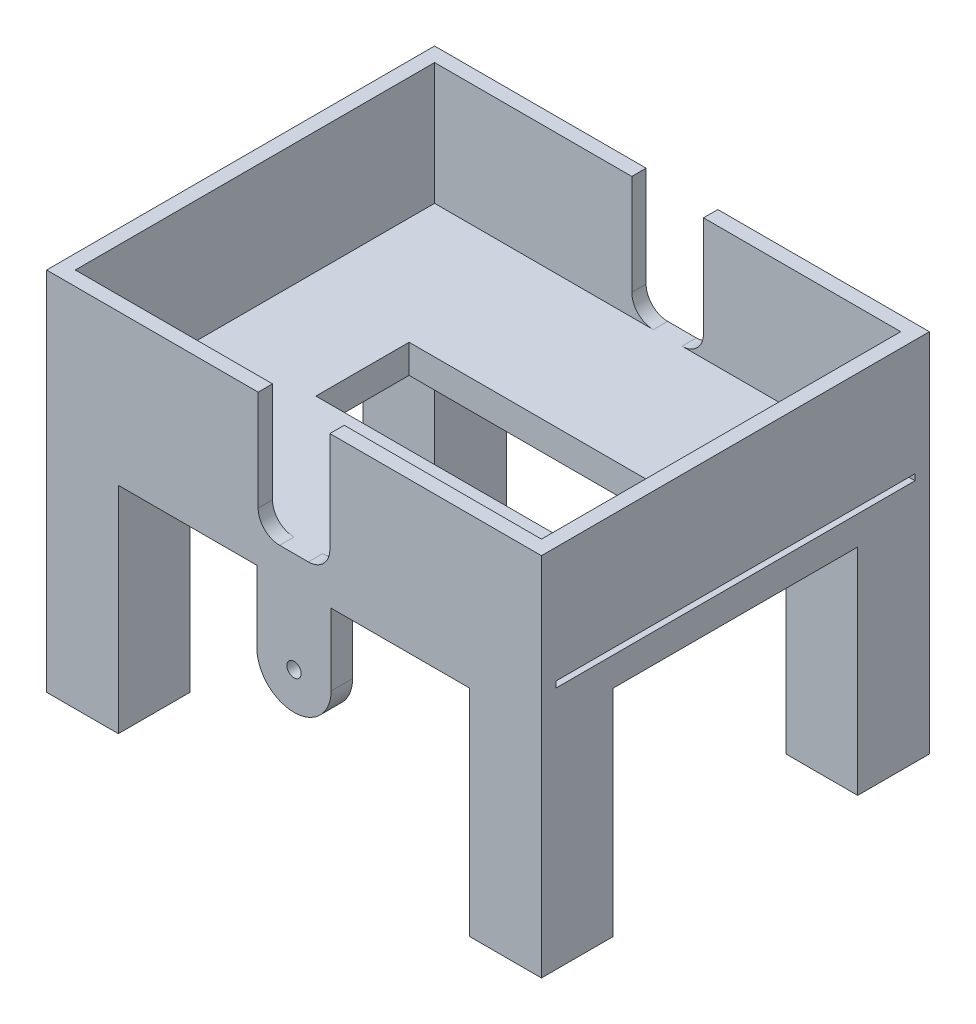
SolidWorks part; units mm, degrees
ref_plane "Front Plane" through (0, 0, 0) normal (0, 0, 1) x (1, 0, 0)
ref_plane "Top Plane" through (0, 0, 0) normal (0, 1, 0) x (1, 0, 0)
ref_plane "Right Plane" through (0, 0, 0) normal (1, 0, 0) x (0, 0, -1)
sketch "Sketch5" plane through (0, 0, 0) normal (0, 1, 0) x (1, 0, 0)
  line L1 (0, 127.254) -> (165.1, 127.254)
  line L2 (0, 127.254) -> (0, 0)
  line L3 (0, 0) -> (165.1, 0)
  line L4 (165.1, 127.254) -> (165.1, 0)
  line L5 (-5.08, 132.334) -> (170.18, 132.334)
  line L6 (-5.08, 132.334) -> (-5.08, -5.08)
  line L7 (-5.08, -5.08) -> (170.18, -5.08)
  line L8 (170.18, 132.334) -> (170.18, -5.08)
  dimension "D1" = 165.1
  dimension "D2" = 127.254
  dimension "D3" = 5.08
  dimension "D4" = 5.08
  dimension "D5" = 5.08
  dimension "D6" = 5.08
extrude "Boss-Extrude2" add sketch "Sketch5" along normal blind 43.18
sketch "Sketch7" plane through (0, 0, 0) normal (0, 1, 0) x (1, 0, 0)
  line L0 (-5.08, -5.08) -> (170.18, -5.08) construction
  line L1 (-5.08, -5.08) -> (170.18, -5.08)
  line L2 (-5.08, -5.08) -> (-5.08, 132.334)
  line L3 (-5.08, 132.334) -> (170.18, 132.334)
  line L4 (170.18, -5.08) -> (170.18, 132.334)
extrude "Boss-Extrude4" add sketch "Sketch7" against normal blind 10.16
sketch "Sketch9" plane through (170.18, 0, 0) normal (1, 0, 0) x (0, 0, -1)
  line L0 (127.254, 0) -> (0, 0) construction
  line L1 (0, 0) -> (127.254, 0)
  line L2 (0, 0) -> (0, 2.159)
  line L3 (0, 2.159) -> (127.254, 2.159)
  line L4 (127.254, 0) -> (127.254, 2.159)
  dimension "D1" = 127.254
  dimension "D2" = 2.159
extrude "Cut-Extrude1" cut sketch "Sketch9" against normal blind 8.128
sketch "Sketch10" plane through (0, 0, 5.08) normal (0, 0, 1) x (1, 0, 0)
  line L0 (170.18, 43.18) -> (170.18, -10.16) construction
  line L1 (69.85, 43.18) -> (95.25, 43.18)
  line L2 (69.85, 43.18) -> (69.85, 7.62)
  line L3 (77.47, 0) -> (87.63, 0)
  line L4 (95.25, 43.18) -> (95.25, 7.62)
  line L5 (82.55, 0) -> (82.55, 43.18) construction
  line L6 (-5.08, 43.18) -> (170.18, 43.18) construction
  arc A0 (87.63, 0) -> (95.25, 7.62) centre (87.63, 7.62) ccw
  arc A1 (69.85, 7.62) -> (77.47, 0) centre (77.47, 7.62) ccw
  point P16 (95.25, 0)
  point P20 (82.55, 0)
  dimension "D5" = 7.62
  dimension "D6" = 7.62
  dimension "D1" = 25.4
  dimension "D2" = 12.7
  dimension "D3" = 87.63
  dimension "D4" = 43.18
extrude "Cut-Extrude2" cut sketch "Sketch10" against normal blind 147.066 and the other way blind 13.208
sketch "Sketch11" plane through (0, -10.16, 0) normal (0, -1, 0) x (1, 0, 0)
  line L1 (38.1, -80.137) -> (127, -80.137)
  line L2 (38.1, -80.137) -> (38.1, -47.117)
  line L3 (38.1, -47.117) -> (127, -47.117)
  line L4 (127, -80.137) -> (127, -47.117)
  line L6 (38.1, -63.627) -> (126.7086, -63.627) construction
  line L8 (87.63, -132.334) -> (77.47, -132.334) construction
  line L9 (82.55, -80.137) -> (82.55, -48.1628) construction
  line L12 (170.18, 5.08) -> (170.18, -132.334) construction
  dimension "D1" = 33.02
  dimension "D2" = 88.9
  dimension "D3" = 68.707
  dimension "D4" = 87.63
extrude "Cut-Extrude3" cut sketch "Sketch11" against normal blind 10.16
sketch "Sketch12" plane through (0, -10.16, 0) normal (0, -1, 0) x (1, 0, 0)
  line L0 (-5.08, 5.08) -> (170.18, 5.08) construction
  line L1 (-5.08, 5.08) -> (20.32, 5.08)
  line L2 (-5.08, 5.08) -> (-5.08, -20.32)
  line L3 (-5.08, -20.32) -> (20.32, -20.32)
  line L4 (20.32, 5.08) -> (20.32, -20.32)
  line L5 (-5.08, -132.334) -> (-5.08, 5.08) construction
  line L6 (170.18, -63.627) -> (-5.08, -63.627) construction
  line L7 (144.78, 5.08) -> (144.78, -20.32)
  line L8 (144.78, 5.08) -> (170.18, 5.08)
  line L9 (170.18, 5.08) -> (170.18, -20.32)
  line L10 (144.78, -20.32) -> (170.18, -20.32)
  line L11 (170.18, 5.08) -> (170.18, -132.334) construction
  line L12 (144.78, -132.334) -> (170.18, -132.334)
  line L13 (170.18, -132.334) -> (170.18, -106.934)
  line L14 (144.78, -106.934) -> (170.18, -106.934)
  line L15 (144.78, -132.334) -> (144.78, -106.934)
  line L16 (-5.08, -106.934) -> (20.32, -106.934)
  line L17 (20.32, -132.334) -> (20.32, -106.934)
  line L18 (-5.08, -132.334) -> (20.32, -132.334)
  line L19 (-5.08, -132.334) -> (-5.08, -106.934)
  dimension "D1" = 25.4
  dimension "D2" = 25.4
  dimension "D3" = 2
extrude "Boss-Extrude5" add sketch "Sketch12" along normal blind 76.2
sketch "Sketch13" plane through (0, -86.36, 0) normal (0, -1, 0) x (1, 0, 0)
  line L0 (20.32, -20.32) -> (20.32, 5.08) construction
  line L1 (-2.54, 2.54) -> (17.78, 2.54)
  line L2 (-2.54, 2.54) -> (-2.54, -17.78)
  line L3 (-2.54, -17.78) -> (17.78, -17.78)
  line L4 (17.78, 2.54) -> (17.78, -17.78)
  line L5 (-5.08, -20.32) -> (20.32, -20.32) construction
  line L6 (-5.08, -7.62) -> (20.32, -7.62) construction
  line L7 (7.62, -20.32) -> (7.62, 5.08) construction
  line L8 (-5.08, 5.08) -> (-5.08, -20.32) construction
  line L9 (20.32, -20.32) -> (20.32, 5.08) construction
  line L10 (20.32, 5.08) -> (-5.08, 5.08) construction
  line L11 (-5.08, -20.32) -> (20.32, -20.32) construction
  line L12 (147.32, 2.54) -> (147.32, -17.78)
  line L13 (147.32, 2.54) -> (167.64, 2.54)
  line L14 (167.64, 2.54) -> (167.64, -17.78)
  line L15 (147.32, -17.78) -> (167.64, -17.78)
  line L16 (157.48, -20.32) -> (157.48, 5.08) construction
  line L17 (144.78, -7.62) -> (170.18, -7.62) construction
  line L18 (-5.08, -63.627) -> (170.18, -63.627) construction
  line L19 (-5.08, -106.934) -> (-5.08, -20.32) construction
  line L20 (170.18, -20.32) -> (170.18, -106.934) construction
  line L21 (147.32, -109.474) -> (167.64, -109.474)
  line L22 (147.32, -129.794) -> (147.32, -109.474)
  line L23 (147.32, -129.794) -> (167.64, -129.794)
  line L24 (167.64, -129.794) -> (167.64, -109.474)
  line L25 (144.78, -119.634) -> (170.18, -119.634) construction
  line L26 (157.48, -106.934) -> (157.48, -132.334) construction
  line L27 (7.62, -106.934) -> (7.62, -132.334) construction
  line L28 (-5.08, -119.634) -> (20.32, -119.634) construction
  line L29 (-2.54, -109.474) -> (17.78, -109.474)
  line L30 (17.78, -129.794) -> (17.78, -109.474)
  line L31 (-2.54, -129.794) -> (17.78, -129.794)
  line L32 (-2.54, -129.794) -> (-2.54, -109.474)
  line L33 (144.78, 5.08) -> (144.78, -20.32) construction
  point P23 (7.62, 2.54)
  point P24 (-2.54, -7.62)
  dimension "D1" = 2.54
  dimension "D2" = 2.54
  dimension "D3" = 2
extrude "Cut-Extrude4" cut sketch "Sketch13" against normal blind 76.2
sketch "Sketch14" plane through (0, 0, 5.08) normal (0, 0, 1) x (1, 0, 0)
  line L0 (82.55, -10.16) -> (82.55, -35.56) construction
  line L3 (69.4092, -10.16) -> (69.4092, -35.56)
  line L4 (20.32, -10.16) -> (144.78, -10.16) construction
  line L5 (95.6908, -10.16) -> (95.6908, -35.56)
  line L8 (69.85, 43.18) -> (69.85, 7.62) construction
  line L9 (69.4092, -10.16) -> (95.6908, -10.16)
  arc A2 (69.4092, -35.56) -> (95.6908, -35.56) centre (82.55, -35.56) ccw
  circle A3 centre (82.55, -35.56) radius 2.54
  dimension "D3" = 5.08
  dimension "D1" = 13.1408
  dimension "D2" = 25.4
extrude "Boss-Extrude6" add sketch "Sketch14" against normal blind 7.62
ref_plane "Plane3" through (0, 0, -63.627) normal (0, 0, 1) x (1, 0, 0)
mirror "Mirror2" about plane through (0, 0, -63.627) normal (0, 0, 1) of "Boss-Extrude6"
sketch "Sketch15" plane through (0, 0, -132.334) normal (0, 0, -1) x (-1, 0, 0)
  line L0 (-170.18, 43.18) -> (-95.25, 43.18) construction
  line L1 (-95.25, 43.18) -> (-95.25, 7.62) construction
  circle A0 centre (-122.428, 13.97) radius 2.54
  point P4 (0, 0)
  point P6 (-115.6357, 13.8246)
  dimension "D3" = 5.08
  dimension "D1" = 29.21
  dimension "D2" = 27.178
extrude "Boss-Extrude7" add sketch "Sketch15" along normal blind 25.4
